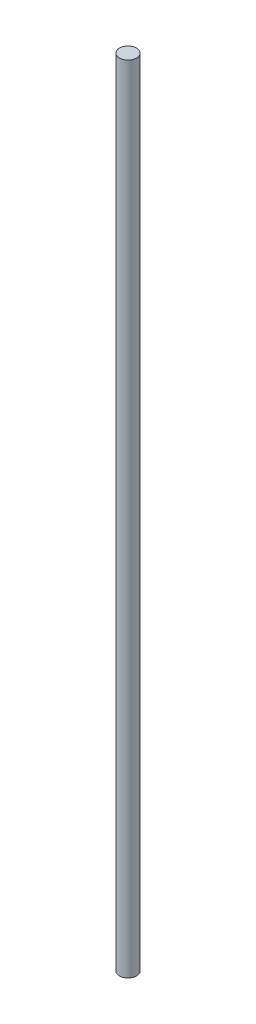
SolidWorks part; units mm, degrees
ref_plane "Front Plane" through (0, 0, 0) normal (0, 0, 1) x (1, 0, 0)
ref_plane "Top Plane" through (0, 0, 0) normal (0, 1, 0) x (1, 0, 0)
ref_plane "Right Plane" through (0, 0, 0) normal (1, 0, 0) x (0, 0, -1)
sketch "Sketch1" plane through (0, 0, 0) normal (0, 1, 0) x (1, 0, 0)
  circle A0 centre (0, 0) radius 4
  dimension "D1" = 8
extrude "Boss-Extrude1" add sketch "Sketch1" along normal blind 370
